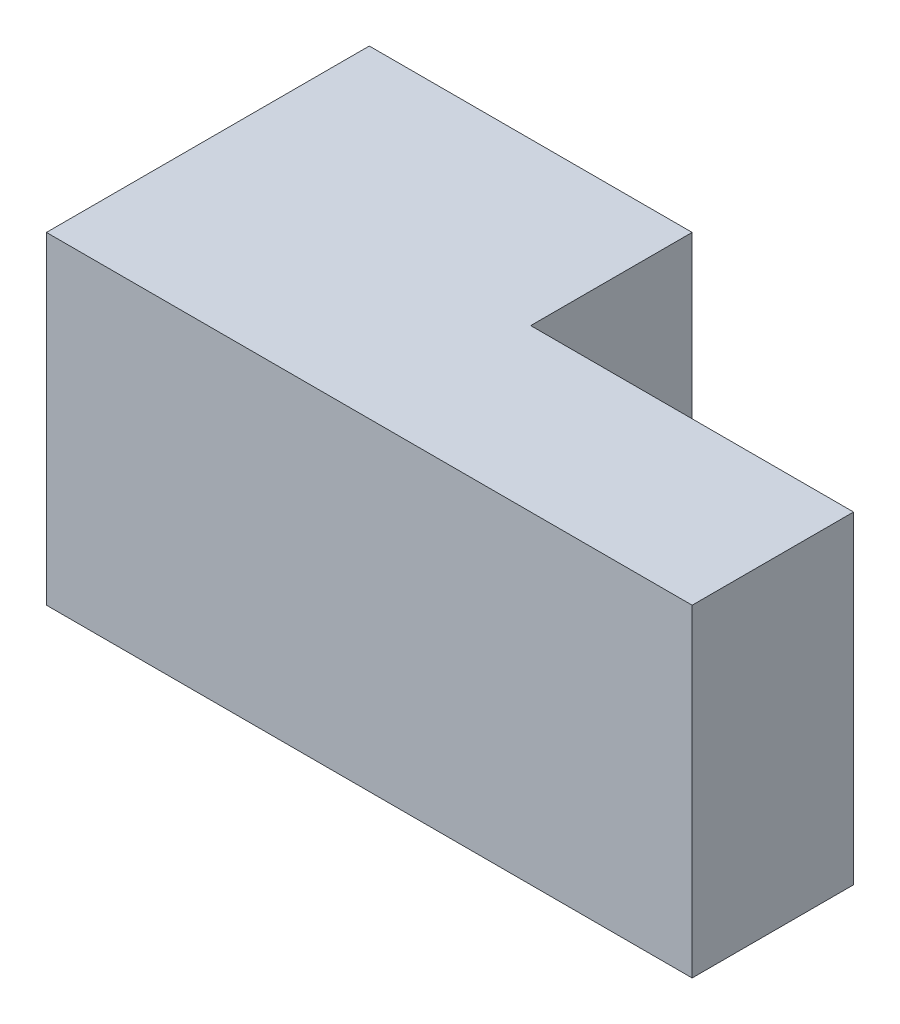
SolidWorks part; units mm, degrees
ref_plane "Front Plane" through (0, 0, 0) normal (0, 0, 1) x (1, 0, 0)
ref_plane "Top Plane" through (0, 0, 0) normal (0, 1, 0) x (1, 0, 0)
ref_plane "Right Plane" through (0, 0, 0) normal (1, 0, 0) x (0, 0, -1)
sketch "Sketch1" plane through (0, 0, 0) normal (0, 0, 1) x (1, 0, 0)
  line L1 (0, 0) -> (12.7, 0)
  line L2 (0, 0) -> (0, 12.7)
  line L3 (0, 12.7) -> (12.7, 12.7)
  line L4 (12.7, 0) -> (12.7, 12.7)
  dimension "D1" = 12.7
extrude "Boss-Extrude1" add sketch "Sketch1" along normal blind 12.7
sketch "Sketch2" plane through (12.7, 0, 0) normal (1, 0, 0) x (0, 0, -1)
  line L0 (-12.7, 0) -> (0, 0) construction
  line L1 (-12.7, 12.7) -> (-6.35, 12.7)
  line L2 (-12.7, 12.7) -> (-12.7, 0)
  line L3 (-12.7, 0) -> (-6.35, 0)
  line L4 (-6.35, 12.7) -> (-6.35, 0)
  dimension "D1" = 6.35
extrude "Boss-Extrude2" add sketch "Sketch2" along normal blind 12.7
